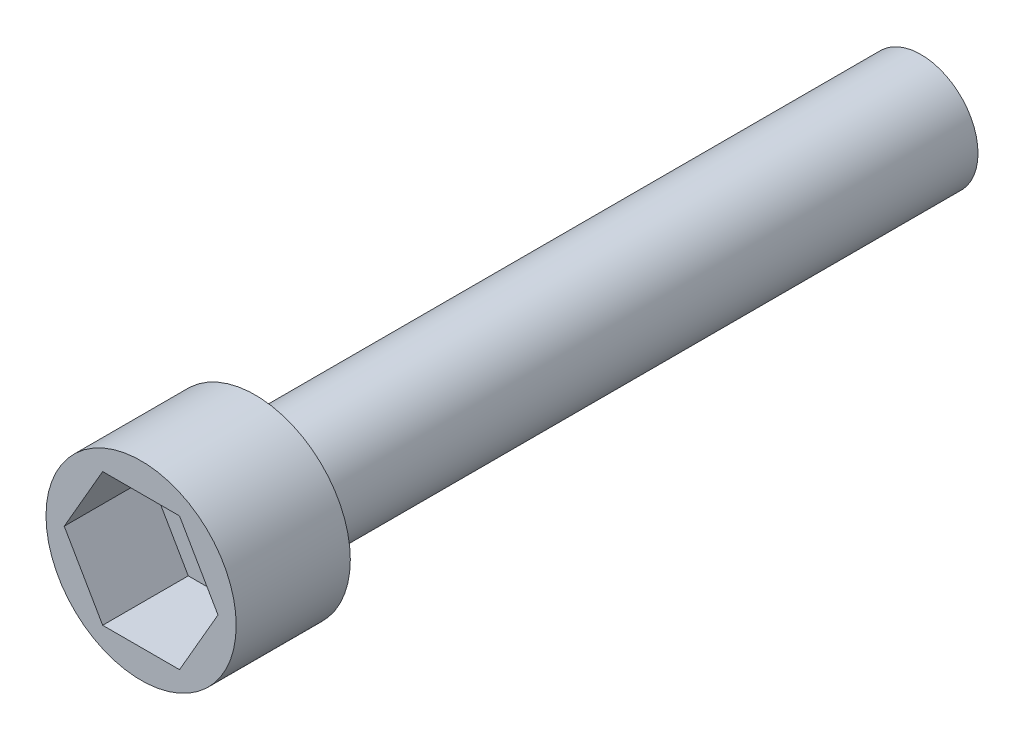
SolidWorks part; units mm, degrees
ref_plane "Plan de face" through (0, 0, 0) normal (0, 0, 1) x (1, 0, 0)
ref_plane "Plan de dessus" through (0, 0, 0) normal (0, 1, 0) x (1, 0, 0)
ref_plane "Plan de droite" through (0, 0, 0) normal (1, 0, 0) x (0, 0, -1)
sketch "Esquisse1" plane through (0, 0, 0) normal (0, 0, 1) x (1, 0, 0)
  circle A0 centre (0, 0) radius 3
  dimension "D1" = 6
extrude "Boss.-Extru.1" add sketch "Esquisse1" along normal blind 35
sketch "Esquisse2" plane through (0, 0, 35) normal (0, 0, 1) x (1, 0, 0)
  circle A0 centre (0, 0) radius 5
  dimension "D1" = 10
extrude "Boss.-Extru.2" add sketch "Esquisse2" along normal blind 6
sketch "Esquisse3" plane through (0, 0, 41) normal (0, 0, 1) x (1, 0, 0)
  line L1 (4.0415, 0) -> (2.0207, 3.5)
  line L2 (2.0207, 3.5) -> (-2.0207, 3.5)
  line L3 (-2.0207, 3.5) -> (-4.0415, 0)
  line L4 (-4.0415, 0) -> (-2.0207, -3.5)
  line L5 (-2.0207, -3.5) -> (2.0207, -3.5)
  line L6 (2.0207, -3.5) -> (4.0415, 0)
  circle A0 centre (0, 0) radius 3.5 construction
  dimension "D1" = 7
extrude "Enlèv. mat.-Extru.1" cut sketch "Esquisse3" against normal blind 4.5
